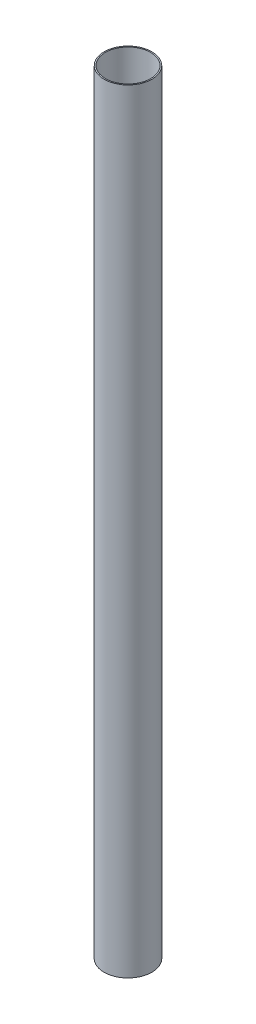
SolidWorks part; units mm, degrees
material "Chrome Stainless Steel"
ref_plane "Front Plane" through (0, 0, 0) normal (0, 0, 1) x (1, 0, 0)
ref_plane "Top Plane" through (0, 0, 0) normal (0, 1, 0) x (1, 0, 0)
ref_plane "Right Plane" through (0, 0, 0) normal (1, 0, 0) x (0, 0, -1)
sketch "Sketch1" plane through (0, 0, 0) normal (0, 1, 0) x (1, 0, 0)
  circle A0 centre (0, 0) radius 15.875
extrude "Boss-Extrude1" add sketch "Sketch1" along normal blind 514
sketch "Sketch2" plane through (0, 0, 0) normal (0, -1, 0) x (1, 0, 0)
  circle A0 centre (0, 0) radius 15.075
  circle A1 centre (0, 0) radius 15.875 construction
  dimension "D1" = 0.8
extrude "Cut-Extrude1" cut sketch "Sketch2" against normal through all
